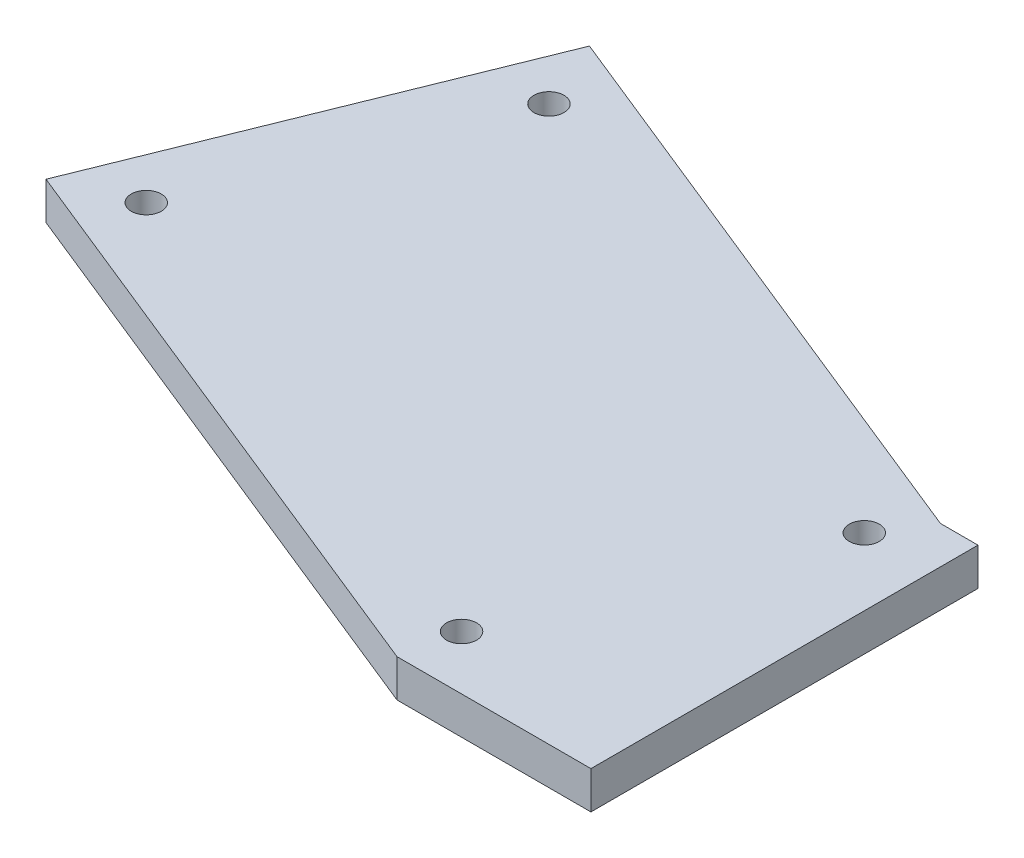
SolidWorks part; units mm, degrees
material "Birch Ply"
ref_plane "Front Plane" through (0, 0, 0) normal (0, 0, 1) x (1, 0, 0)
ref_plane "Top Plane" through (0, 0, 0) normal (0, 1, 0) x (1, 0, 0)
ref_plane "Right Plane" through (0, 0, 0) normal (1, 0, 0) x (0, 0, -1)
sketch "Sketch1" plane through (0, 0, 0) normal (0, 1, 0) x (1, 0, 0)
  line L0 (0, 0) -> (-3.175, 0)
  line L1 (-3.175, 0) -> (-52.984, 20.1241)
  line L2 (-52.984, 20.1241) -> (-66.2098, -12.611)
  line L3 (-66.2098, -12.611) -> (-16.4009, -32.7352)
  line L4 (-3.175, 0) -> (-3.175, -32.7352) construction
  line L5 (0, 0) -> (0, -32.7352)
  line L6 (0, -32.7352) -> (-16.4009, -32.7352)
  line L7 (-3.175, 0) -> (-16.4009, -32.7352) construction
  line L9 (-5.7117, -3.9062) -> (-15.5122, -28.1632) construction
  line L10 (-15.5122, -28.1632) -> (-60.258, -10.0846) construction
  line L11 (-60.258, -10.0846) -> (-50.4576, 14.1723) construction
  line L12 (-50.4576, 14.1723) -> (-5.7117, -3.9062) construction
  circle A0 centre (-50.4576, 14.1723) radius 1.27
  circle A1 centre (-60.258, -10.0846) radius 1.27
  circle A2 centre (-15.5122, -28.1632) radius 1.27
  circle A3 centre (-5.7117, -3.9062) radius 1.27
  circle A4 centre (-5.7117, -3.9062) radius 4.572 construction
  circle A5 centre (-15.5122, -28.1632) radius 4.572 construction
  circle A6 centre (-50.4576, 14.1723) radius 4.572 construction
  circle A7 centre (-60.258, -10.0846) radius 4.572 construction
  point P2 (0, -16.3676)
  dimension "D5" = 2.54
  dimension "D6" = 2.54
  dimension "D7" = 2.54
  dimension "D8" = 2.54
  dimension "D9" = 9.144
  dimension "D12" = 9.144
  dimension "D13" = 9.144
  dimension "D14" = 9.144
  dimension "D1" = 3.175
  dimension "D3" = 112
  dimension "D10" = 48.26
  dimension "D11" = 26.162
extrude "Boss-Extrude1" add sketch "Sketch1" along normal blind 3.175
equation "\"D6@Sketch1\"=\"D5@Sketch1\""
equation "\"D8@Sketch1\"=\"D5@Sketch1\""
equation "\"D7@Sketch1\"=\"D5@Sketch1\""
equation "\"D9@Sketch1\"=\"D13@Sketch1\""
equation "\"D12@Sketch1\"=\"D13@Sketch1\""
equation "\"D14@Sketch1\"=\"D13@Sketch1\""
